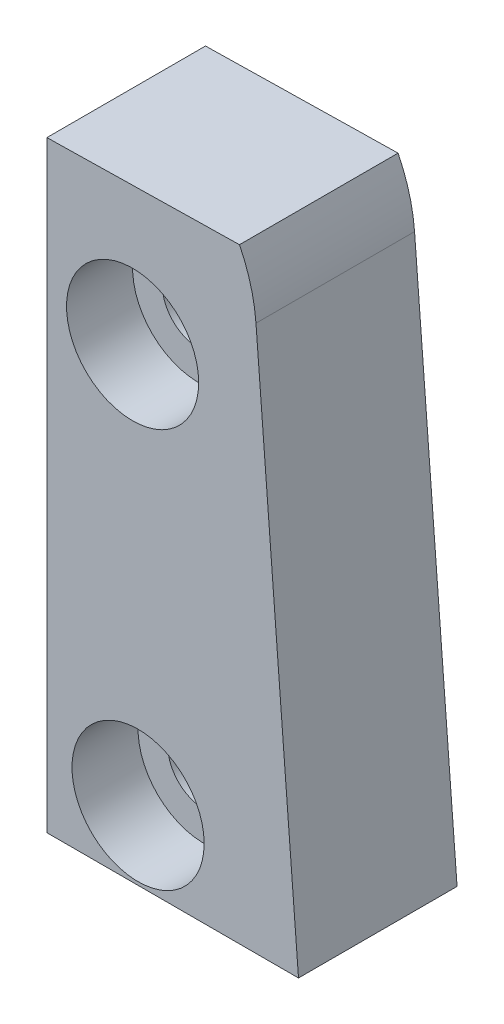
SolidWorks part; units mm, degrees
ref_plane "Front Plane" through (0, 0, 0) normal (1, 0, 0) x (0, 1, 0)
ref_plane "Top Plane" through (0, 0, 0) normal (0, 0, 1) x (0, 1, 0)
ref_plane "Right Plane" through (0, 0, 0) normal (0, 1, 0) x (-1, 0, 0)
sketch "Sketch1" plane through (0, 0, 0) normal (0, 0, 1) x (0, 1, 0)
  line L0 (6.83, -2.3448) -> (-9.6907, -3.6318)
  line L1 (7.2691, 3.9596) -> (8.5318, 3.9826)
  line L2 (-9.6907, -3.6318) -> (-9.6907, -2.2054)
  line L3 (8.5318, 3.9826) -> (8.6382, -1.8458)
  line L4 (-9.6907, 3.1951) -> (6.8764, 3.4236) construction
  line L5 (6.8764, 3.4236) -> (6.9454, -1.5759) construction
  line L6 (6.9454, -1.5759) -> (-9.6907, -1.8054) construction
  line L7 (-9.6907, -2.2054) -> (6.9475, -1.9759)
  line L8 (6.9475, -1.9759) -> (7.3509, -1.9703)
  line L9 (7.3509, -1.9703) -> (7.2691, 3.9596)
  arc A0 (6.83, -2.3448) -> (8.6382, -1.8458) centre (6.4473, 2.5673) ccw
  circle A1 centre (-7.5946, 1.2238) radius 1.1 construction
  circle A2 centre (4.4042, 1.3893) radius 1.1 construction
  point P0 (-0.6778, 0.862)
  dimension "D1" = 2.2
  dimension "D5" = 4.927
  dimension "D8" = 2.2
  dimension "D4" = 5.8284
  dimension "D6" = 16.5207
  dimension "D7" = 1.287
  dimension "D9" = 12
  dimension "D10" = 5.5287
  dimension "D12" = 0.4
  dimension "D13" = 0.4
  dimension "D14" = 0.4
extrude "Boss-Extrude1" add sketch "Sketch1" along normal blind 1.8
sketch "Sketch3" plane through (0, 0, 1.8) normal (0, 0, 1) x (1, 0, 0)
  line L0 (-3.9826, 8.5318) -> (-3.9826, -9.6907)
  line L1 (-3.9826, -9.6907) -> (3.6318, -9.6907)
  line L2 (3.6318, -9.6907) -> (2.3448, 6.83)
  line L3 (-3.9826, 8.5318) -> (1.8458, 8.6382)
  circle A0 centre (-1.2238, -7.5946) radius 1.1
  circle A1 centre (-1.3893, 4.4042) radius 1.1
  arc A3 (2.3448, 6.83) -> (1.8458, 8.6382) centre (-2.5673, 6.4473) ccw
extrude "Boss-Extrude2" add sketch "Sketch3" along normal blind 3
sketch "Sketch4" plane through (0, 0, 1.8) normal (0, 0, -1) x (1, 0, 0)
  line L1 (-0.29, 5.1999) -> (-0.29, -1.9694)
  line L2 (-0.29, 5.1999) -> (-2.9536, 5.1999)
  line L3 (-2.9536, 5.1999) -> (-2.9536, -1.9694)
  line L4 (-0.29, -1.9694) -> (-2.9536, -1.9694)
  line L5 (-0.29, 5.1999) -> (-2.9536, -1.9694) construction
  line L6 (-2.9536, 5.1999) -> (-0.29, -1.9694) construction
  point P2 (-1.6218, 1.6153)
extrude "Cut-Extrude1" cut sketch "Sketch4" against normal blind 2
sketch "Sketch5" plane through (0, 0, 4.8) normal (0, 0, 1) x (1, 0, 0)
  circle A0 centre (-1.3893, 4.4042) radius 2
  circle A1 centre (-1.2238, -7.5946) radius 2
  dimension "D1" = 4
  dimension "D2" = 4
extrude "Cut-Extrude2" cut sketch "Sketch5" against normal blind 2
